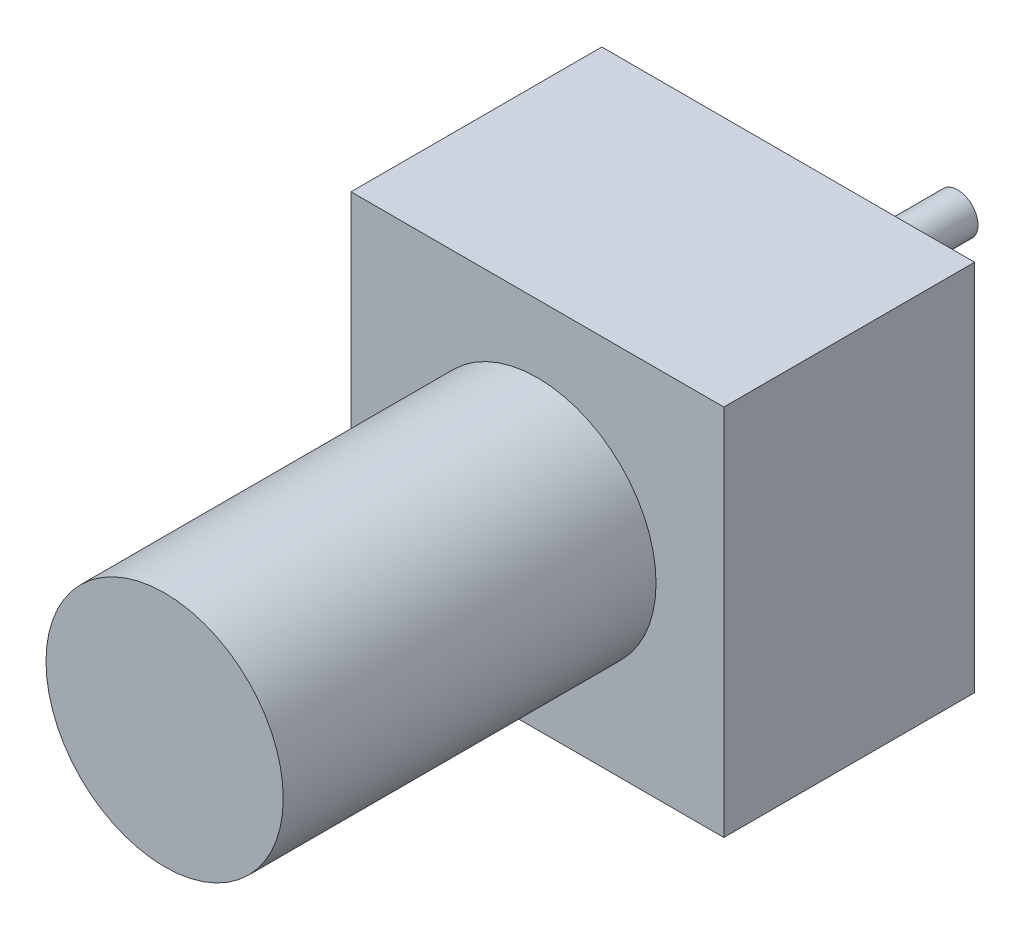
SolidWorks part; units mm, degrees
ref_plane "Front Plane" through (0, 0, 0) normal (0, 0, 1) x (1, 0, 0)
ref_plane "Top Plane" through (0, 0, 0) normal (0, 1, 0) x (1, 0, 0)
ref_plane "Right Plane" through (0, 0, 0) normal (1, 0, 0) x (0, 0, -1)
sketch "Sketch1" plane through (0, 0, 0) normal (0, 0, 1) x (1, 0, 0)
  line L1 (-27.5, 27.5) -> (27.5, 27.5)
  line L2 (-27.5, 27.5) -> (-27.5, -27.5)
  line L3 (-27.5, -27.5) -> (27.5, -27.5)
  line L4 (27.5, 27.5) -> (27.5, -27.5)
  line L5 (-27.5, 27.5) -> (27.5, -27.5) construction
  line L6 (-27.5, -27.5) -> (27.5, 27.5) construction
  point P0 (0, 0)
  dimension "D1" = 55
  dimension "D2" = 55
extrude "Boss-Extrude1" add sketch "Sketch1" along normal blind 37
sketch "Sketch2" plane through (0, 0, 37) normal (0, 0, 1) x (1, 0, 0)
  circle A0 centre (0, 0) radius 17.5
  dimension "D1" = 35
extrude "Boss-Extrude2" add sketch "Sketch2" along normal blind 55
sketch "Sketch3" plane through (0, 0, 0) normal (0, 0, -1) x (-1, 0, 0)
  line L0 (27.5, -27.5) -> (-27.5, -27.5) construction
  circle A0 centre (0, 7.5) radius 3
  dimension "D1" = 6
  dimension "D2" = 35
extrude "Boss-Extrude3" add sketch "Sketch3" along normal blind 25
